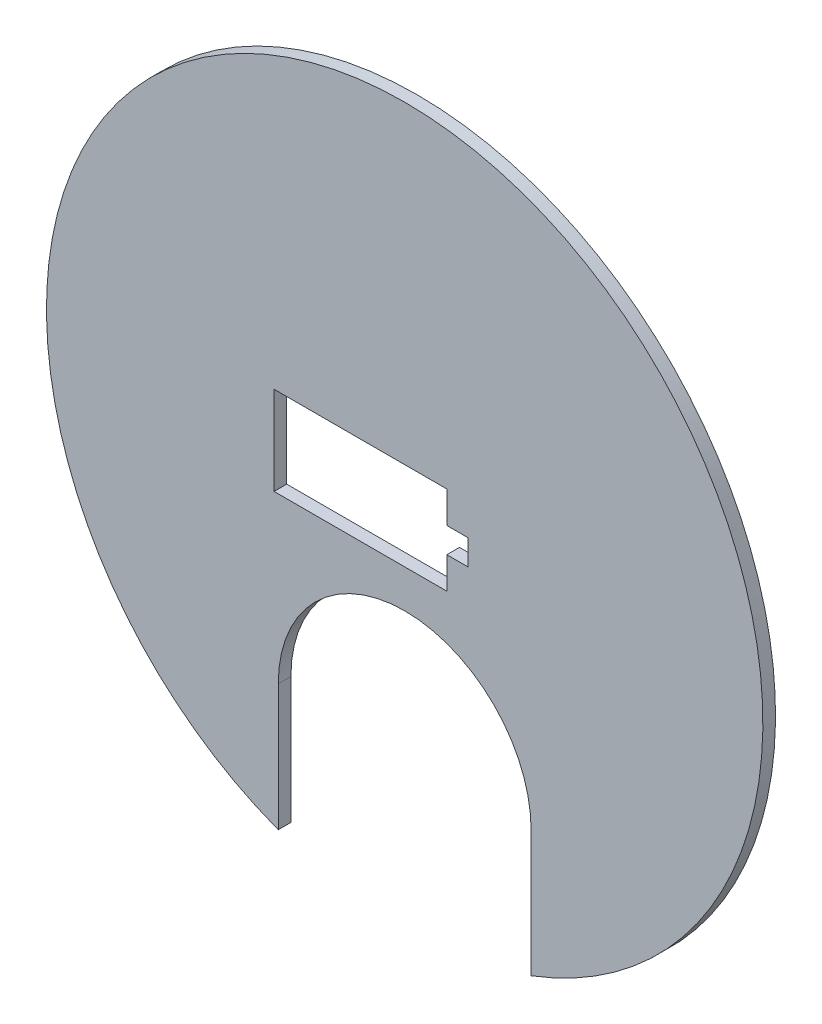
SolidWorks part; units mm, degrees
ref_plane "Plan de face" through (0, 0, 0) normal (0, 0, 1) x (1, 0, 0)
ref_plane "Plan de dessus" through (0, 0, 0) normal (0, 1, 0) x (1, 0, 0)
ref_plane "Plan de droite" through (0, 0, 0) normal (1, 0, 0) x (0, 0, -1)
sketch "Esquisse1" plane through (0, 0, 0) normal (0, 0, 1) x (1, 0, 0)
  circle A0 centre (-11.1979, 8.2445) radius 85
  dimension "D1" = 170
extrude "Boss.-Extru.1" add sketch "Esquisse1" along normal blind 3
sketch "Esquisse2" plane through (0, 0, 0) normal (0, 0, -1) x (-1, 0, 0)
  line L0 (11.1979, 93.2445) -> (11.1979, -76.7555) construction
  line L1 (96.1979, 8.2445) -> (-73.8021, 8.2445) construction
  line L2 (1.1979, 5.2445) -> (1.1979, -2.2555)
  line L3 (1.1979, 18.7445) -> (42.1979, 18.7445)
  line L4 (1.1979, 18.7445) -> (1.1979, 11.2445)
  line L5 (1.1979, -2.2555) -> (42.1979, -2.2555)
  line L6 (42.1979, 18.7445) -> (42.1979, -2.2555)
  line L7 (-3.8021, 11.2445) -> (1.1979, 11.2445)
  line L8 (-3.8021, 11.2445) -> (-3.8021, 5.2445)
  line L9 (-3.8021, 5.2445) -> (1.1979, 5.2445)
  circle A0 centre (11.1979, 8.2445) radius 85 construction
  circle A1 centre (11.1979, 8.2445) radius 1
  dimension "D1" = 2
  dimension "D4" = 10.5
  dimension "D2" = 41
  dimension "D3" = 21
  dimension "D5" = 10
  dimension "D6" = 5
  dimension "D7" = 6
  dimension "D8" = 7.5
extrude "Enlèv. mat.-Extru.1" cut sketch "Esquisse2" against normal blind 3 contours L8 L9 L2 L5 L6 L3 L4 L7 A1 | A1
sketch "Esquisse3" plane through (0, 0, 0) normal (0, 0, -1) x (-1, 0, 0)
  line L0 (11.1979, 93.2445) -> (11.1979, -76.7555) construction
  line L1 (-18.8021, -71.2854) -> (-18.8021, -41.2854)
  line L3 (41.1979, -41.2854) -> (41.1979, -71.2854)
  circle A0 centre (11.1979, 8.2445) radius 85 construction
  arc A1 (-18.8021, -41.2854) -> (41.1979, -41.2854) centre (11.1979, -41.2854) cw
  arc A2 (-18.8021, -71.2854) -> (41.1979, -71.2854) centre (11.1979, 8.2445) ccw
  dimension "D5" = 30
  dimension "D1" = 60
  dimension "D2" = 30
  dimension "D3" = 30
extrude "Enlèv. mat.-Extru.10" cut sketch "Esquisse3" against normal blind 3
